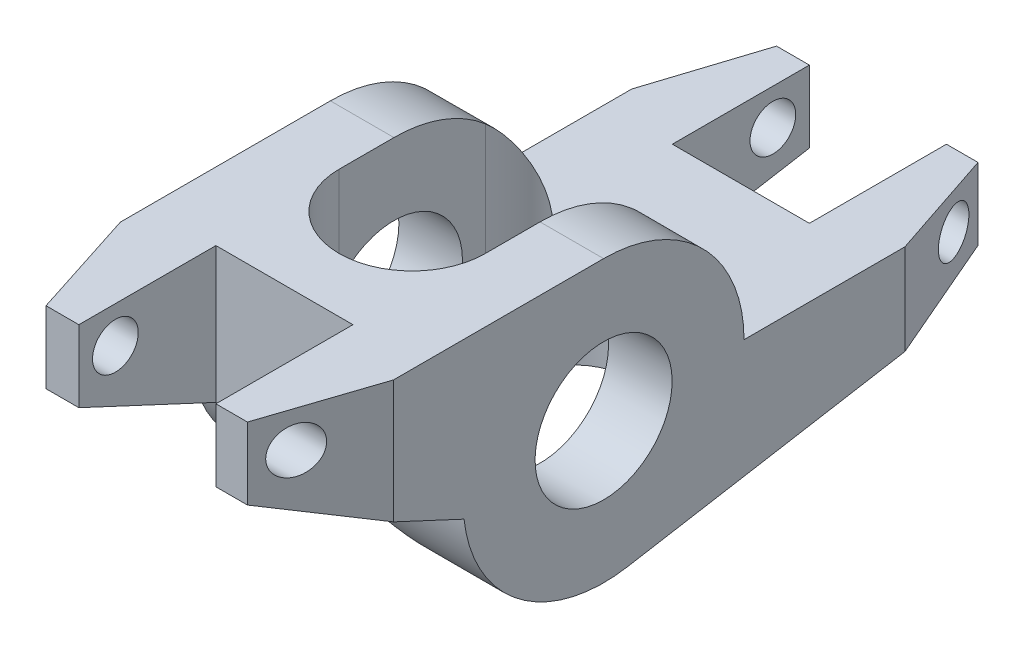
SolidWorks part; units mm, degrees
material "1023 Carbon Steel Sheet (SS)"
ref_plane "Front Plane" through (0, 0, 0) normal (0, 0, 1) x (1, 0, 0)
ref_plane "Top Plane" through (0, 0, 0) normal (0, 1, 0) x (1, 0, 0)
ref_plane "Right Plane" through (0, 0, 0) normal (1, 0, 0) x (0, 0, -1)
sketch "Sketch1" plane through (0, 0, 0) normal (1, 0, 0) x (0, 0, -1)
  line L0 (0, 9.765) -> (-22.225, 9.765)
  line L1 (-22.225, 9.765) -> (-22.225, 4.765)
  line L2 (-22.225, 4.765) -> (-9.7059, -1.0728)
  line L3 (9.765, 0) -> (28.575, 0)
  line L4 (28.575, 0) -> (28.575, -5)
  line L5 (28.575, -5) -> (1.653, -9.6241)
  circle A0 centre (0, 0) radius 4.765
  arc A1 (-9.7059, -1.0728) -> (1.653, -9.6241) centre (0, 0) ccw
  circle A2 centre (0, 0) radius 9.765 construction
  arc A3 (9.765, 0) -> (0, 9.765) centre (0, 0) ccw
  dimension "D1" = 9.53
  dimension "D3" = 22.225
  dimension "D4" = 5
  dimension "D5" = 25
  dimension "D6" = 28.575
  dimension "D7" = 5
  dimension "D2" = 5
extrude "Boss-Extrude1" add sketch "Sketch1" along normal mid plane 19
chamfer "Chamfer1" distance 2.54 distance2 7.62 2 edges at (9.5, -2.5, -28.575) (9.5, 7.265, 22.225)
chamfer "Chamfer2" distance 7.62 distance2 2.45 2 edges at (-9.5, 7.265, 22.225) (-9.5, -2.5, -28.575)
sketch "Sketch2" plane through (0, 0, 0) normal (0, 1, 0) x (1, 0, 0)
  line L0 (0, 6.35) -> (0, -3.81) construction
  line L1 (5.08, 6.35) -> (5.08, -3.81)
  line L2 (-5.08, 6.35) -> (-5.08, -3.81)
  arc A0 (5.08, 6.35) -> (-5.08, 6.35) centre (0, 6.35) ccw
  arc A1 (-5.08, -3.81) -> (5.08, -3.81) centre (0, -3.81) ccw
  point P3 (0, 1.27)
  dimension "D1" = 10.16
  dimension "D2" = 10.16
  dimension "D3" = 3.81
extrude "Cut-Extrude1" cut sketch "Sketch2" against normal mid plane 35
sketch "Sketch3" plane through (0, 0, 0) normal (0, 1, 0) x (1, 0, 0)
  line L0 (6.96, 28.575) -> (-7.05, 28.575) construction
  line L1 (4.765, 19.045) -> (-4.765, 19.045)
  line L2 (4.765, 19.045) -> (4.765, 28.575)
  line L3 (4.765, 28.575) -> (-4.765, 28.575)
  line L4 (-4.765, 19.045) -> (-4.765, 28.575)
  line L5 (4.765, 19.045) -> (-4.765, 28.575) construction
  line L6 (4.765, 28.575) -> (-4.765, 19.045) construction
  line L8 (4.765, -22.225) -> (-4.765, -22.225)
  line L9 (4.765, -22.225) -> (4.765, -12.695)
  line L10 (4.765, -12.695) -> (-4.765, -12.695)
  line L11 (-4.765, -22.225) -> (-4.765, -12.695)
  line L12 (4.765, -22.225) -> (-4.765, -12.695) construction
  line L13 (4.765, -12.695) -> (-4.765, -22.225) construction
  line L14 (6.96, -22.225) -> (-7.05, -22.225) construction
  point P0 (0, 23.81)
  point P7 (0, -17.46)
  dimension "D1" = 9.53
  dimension "D2" = 9.53
  dimension "D3" = 9.53
  dimension "D4" = 9.53
extrude "Cut-Extrude2" cut sketch "Sketch3" against normal mid plane 35
sketch "Sketch4" plane through (0, 0, 0) normal (1, 0, 0) x (0, 0, -1)
  line L0 (28.575, 0) -> (28.575, -5) construction
  line L1 (20.955, 0) -> (28.575, 0) construction
  line L2 (-22.225, 4.765) -> (-22.225, 9.765) construction
  line L3 (-22.225, 9.765) -> (-14.605, 9.765) construction
  circle A0 centre (-19.685, 7.225) radius 1.59
  circle A1 centre (26.035, -2.5) radius 1.59
  dimension "D1" = 3.18
  dimension "D2" = 2.54
  dimension "D3" = 2.5
  dimension "D4" = 2.54
  dimension "D5" = 2.54
extrude "Cut-Extrude3" cut sketch "Sketch4" against normal mid plane 35
